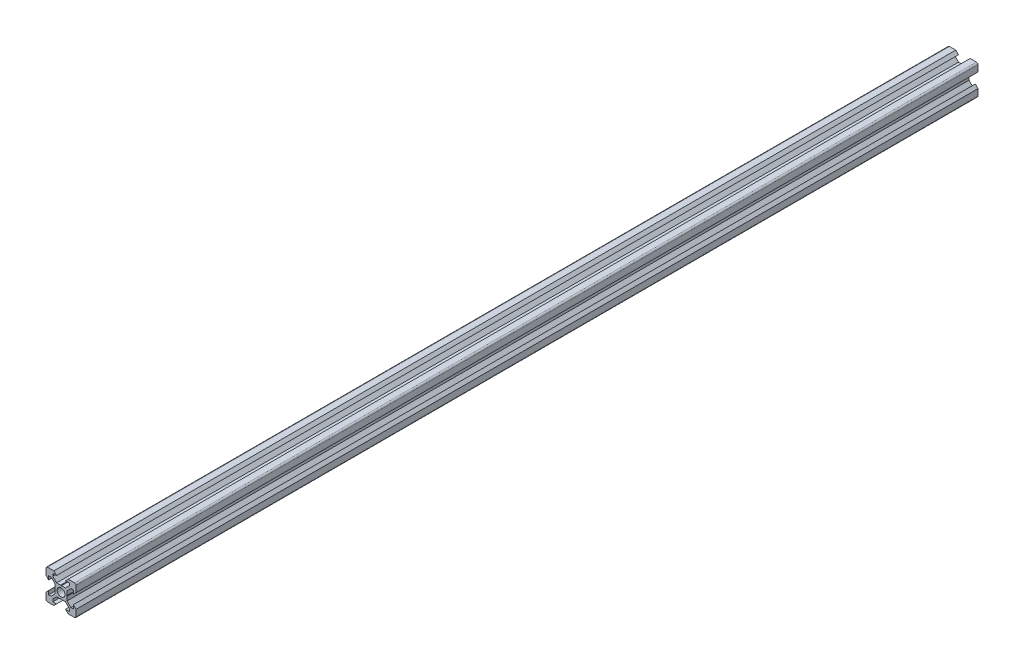
SolidWorks part; units mm, degrees
material "1060-H12 Rod (SS)"
ref_plane "Front Plane" through (0, 0, 0) normal (0, 0, 1) x (1, 0, 0)
ref_plane "Top Plane" through (0, 0, 0) normal (0, 1, 0) x (1, 0, 0)
ref_plane "Right Plane" through (0, 0, 0) normal (1, 0, 0) x (0, 0, -1)
sketch "Sketch1" plane through (0, 0, 0) normal (0, 0, 1) x (1, 0, 0)
  line B0 (10.3368, -8.1134) -> (10.3368, -3.9134)
  line B1 (10.3368, -3.9134) -> (8.5368, -2.1134)
  line B2 (8.5368, -2.1134) -> (8.5368, -4.6134)
  line B3 (8.5368, -4.6134) -> (6.8974, -4.6134)
  line B4 (6.8974, -4.6134) -> (4.3368, -2.0527)
  line B5 (4.3368, -2.0527) -> (4.3368, 0.5866)
  line B6 (4.3368, 0.5866) -> (4.0368, 0.8866)
  line B7 (4.0368, 0.8866) -> (4.3368, 1.1866)
  line B8 (4.3368, 1.1866) -> (4.3368, 3.826)
  line B9 (4.3368, 3.826) -> (6.8974, 6.3866)
  line B10 (6.8974, 6.3866) -> (8.5368, 6.3866)
  line B11 (8.5368, 6.3866) -> (8.5368, 3.8866)
  line B12 (8.5368, 3.8866) -> (10.3368, 5.6866)
  line B13 (10.3368, 5.6866) -> (10.3368, 9.8866)
  line B14 (9.3368, 10.8866) -> (5.1368, 10.8866)
  line B15 (5.1368, 10.8866) -> (3.3368, 9.0866)
  line B16 (3.3368, 9.0866) -> (5.8368, 9.0866)
  line B17 (5.8368, 9.0866) -> (5.8368, 7.4473)
  line B18 (5.8368, 7.4473) -> (3.2761, 4.8866)
  line B19 (3.2761, 4.8866) -> (0.6368, 4.8866)
  line B20 (0.6368, 4.8866) -> (0.3368, 4.5866)
  line B21 (0.3368, 4.5866) -> (0.0368, 4.8866)
  line B22 (0.0368, 4.8866) -> (-2.6026, 4.8866)
  line B23 (-2.6026, 4.8866) -> (-5.1632, 7.4473)
  line B24 (-5.1632, 7.4473) -> (-5.1632, 9.0866)
  line B25 (-5.1632, 9.0866) -> (-2.6632, 9.0866)
  line B26 (-2.6632, 9.0866) -> (-4.4632, 10.8866)
  line B27 (-4.4632, 10.8866) -> (-8.6632, 10.8866)
  line B28 (-9.6632, 9.8866) -> (-9.6632, 5.6866)
  line B29 (-9.6632, 5.6866) -> (-7.8632, 3.8866)
  line B30 (-7.8632, 3.8866) -> (-7.8632, 6.3866)
  line B31 (-7.8632, 6.3866) -> (-6.2239, 6.3866)
  line B32 (-6.2239, 6.3866) -> (-3.6632, 3.826)
  line B33 (-3.6632, 3.826) -> (-3.6632, 1.1866)
  line B34 (-3.6632, 1.1866) -> (-3.3632, 0.8866)
  line B35 (-3.3632, 0.8866) -> (-3.6632, 0.5866)
  line B36 (-3.6632, 0.5866) -> (-3.6632, -2.0527)
  line B37 (-3.6632, -2.0527) -> (-6.2239, -4.6134)
  line B38 (-6.2239, -4.6134) -> (-7.8632, -4.6134)
  line B39 (-7.8632, -4.6134) -> (-7.8632, -2.1134)
  line B40 (-7.8632, -2.1134) -> (-9.6632, -3.9134)
  line B41 (-9.6632, -3.9134) -> (-9.6632, -8.1134)
  line B42 (-8.6632, -9.1134) -> (-4.4632, -9.1134)
  line B43 (-4.4632, -9.1134) -> (-2.6632, -7.3134)
  line B44 (-2.6632, -7.3134) -> (-5.1632, -7.3134)
  line B45 (-5.1632, -7.3134) -> (-5.1632, -5.674)
  line B46 (-5.1632, -5.674) -> (-2.6026, -3.1134)
  line B47 (-2.6026, -3.1134) -> (0.0368, -3.1134)
  line B48 (0.0368, -3.1134) -> (0.3368, -2.8134)
  line B49 (0.3368, -2.8134) -> (0.6368, -3.1134)
  line B50 (0.6368, -3.1134) -> (3.2761, -3.1134)
  line B51 (3.2761, -3.1134) -> (5.8368, -5.674)
  line B52 (5.8368, -5.674) -> (5.8368, -7.3134)
  line B53 (5.8368, -7.3134) -> (3.3368, -7.3134)
  line B54 (3.3368, -7.3134) -> (5.1368, -9.1134)
  line B55 (5.1368, -9.1134) -> (9.3368, -9.1134)
  arc B56 (9.3368, -9.1134) -> (10.3368, -8.1134) centre (9.3368, -8.1134) ccw
  arc B57 (10.3368, 9.8866) -> (9.3368, 10.8866) centre (9.3368, 9.8866) ccw
  arc B58 (-8.6632, 10.8866) -> (-9.6632, 9.8866) centre (-8.6632, 9.8866) ccw
  arc B59 (-9.6632, -8.1134) -> (-8.6632, -9.1134) centre (-8.6632, -8.1134) ccw
  circle B60 centre (0.3368, 0.8866) radius 2.6
sketch_block_instance "AL profile  block  -1"
sketch_block "AL profile  block  " parameters "D1"=5.6128
extrude "Boss-Extrude1" add sketch "Sketch1" along normal blind 600
